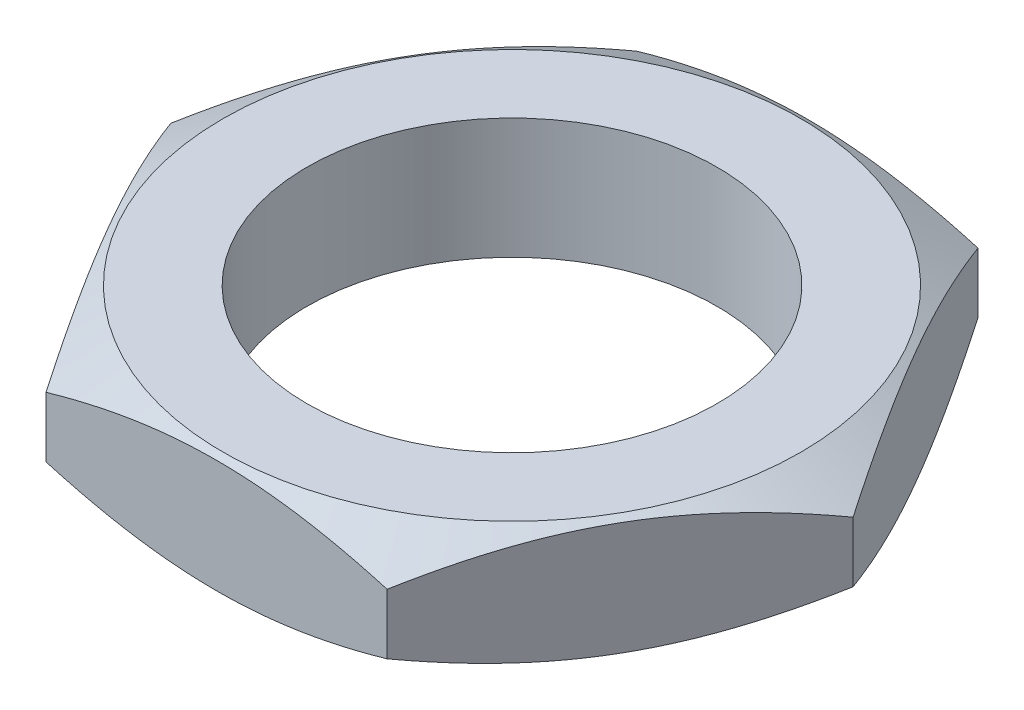
SolidWorks part; units mm, degrees
material "1023 Carbon Steel Sheet (SS)"
ref_plane "Front Plane" through (0, 0, 0) normal (0, 0, 1) x (1, 0, 0)
ref_plane "Top Plane" through (0, 0, 0) normal (0, 1, 0) x (1, 0, 0)
ref_plane "Right Plane" through (0, 0, 0) normal (1, 0, 0) x (0, 0, -1)
sketch "Sketch1" plane through (0, 0, 0) normal (0, 1, 0) x (1, 0, 0)
  line L1 (5.658, 0) -> (2.829, 4.9)
  line L2 (2.829, 4.9) -> (-2.829, 4.9)
  line L3 (-2.829, 4.9) -> (-5.658, 0)
  line L4 (-5.658, 0) -> (-2.829, -4.9)
  line L5 (-2.829, -4.9) -> (2.829, -4.9)
  line L6 (2.829, -4.9) -> (5.658, 0)
  circle A0 centre (0, 0) radius 4.9 construction
  circle A1 centre (0, 0) radius 3.4
  dimension "D2" = 6.8
  dimension "D1" = 9.8
extrude "Boss-Extrude1" add sketch "Sketch1" along normal blind 2
sketch "Sketch2" plane through (0, 0, 0) normal (0, 0, 1) x (1, 0, 0)
  line L0 (0, -1000) -> (0, 49000) construction
  line L1 (-2.829, 0) -> (2.829, 0) construction
  line L2 (5.658, 1.5) -> (4.792, 2)
  line L3 (5.658, 2) -> (5.658, 0) construction
  line L4 (2.829, 2) -> (5.658, 2) construction
  line L5 (4.792, 2) -> (5.658, 2)
  line L6 (5.658, 2) -> (5.658, 1.5)
  line L7 (-5.658, 2) -> (-5.658, 0) construction
  line L8 (-1005.658, 1) -> (48994.342, 1) construction
  line L9 (5.658, 0.5) -> (4.792, 0)
  line L10 (5.658, 0) -> (5.658, 0.5)
  line L11 (4.792, 0) -> (5.658, 0)
  point P5 (0, 0)
  point P11 (-5.658, 1)
  dimension "D1" = 60
  dimension "D2" = 0.5
revolve "Cut-Revolve1" cut sketch "Sketch2" angle 360 about L0
